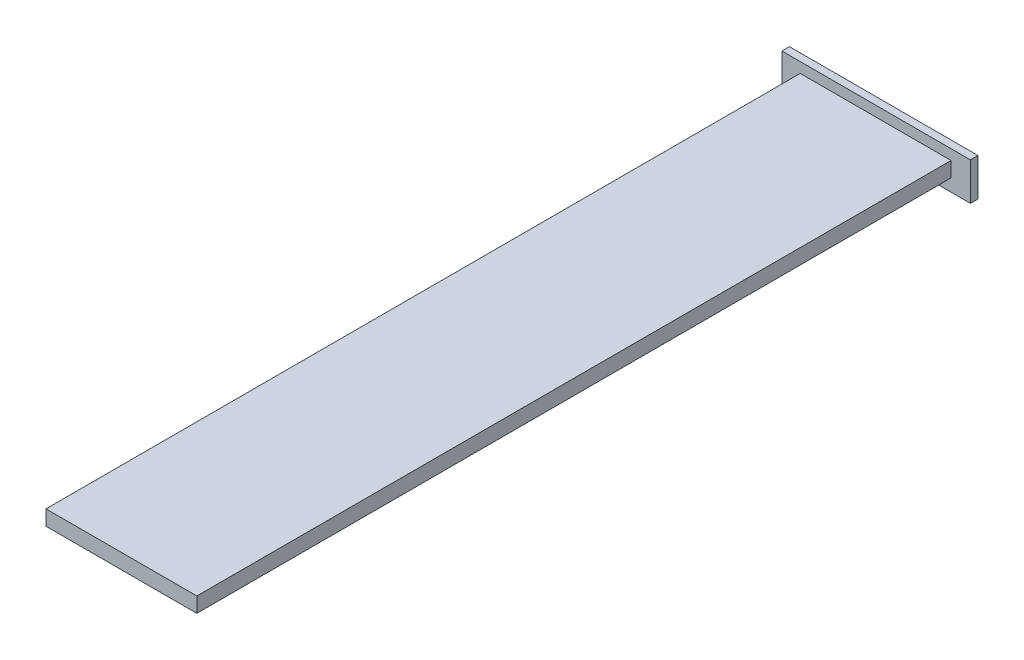
SolidWorks part; units mm, degrees
material "AISI 1010 Aço, barra laminada a quente"
ref_plane "Plano frontal" through (0, 0, 0) normal (0, 0, 1) x (1, 0, 0)
ref_plane "Plano superior" through (0, 0, 0) normal (0, 1, 0) x (1, 0, 0)
ref_plane "Plano direito" through (0, 0, 0) normal (1, 0, 0) x (0, 0, -1)
sketch "Esboço2" plane through (0, 0, 0) normal (0, 0, 1) x (1, 0, 0)
  line L1 (0, 0) -> (250, 0)
  line L2 (0, 0) -> (0, 50)
  line L3 (0, 50) -> (250, 50)
  line L4 (250, 0) -> (250, 50)
  dimension "D1" = 50
  dimension "D2" = 250
extrude "Ressalto-extrusão1" add sketch "Esboço2" along normal blind 10
sketch "Esboço4" plane through (0, 0, 10) normal (0, 0, 1) x (1, 0, 0)
  line L1 (24.2879, 36.4076) -> (224.2879, 36.4076)
  line L2 (24.2879, 36.4076) -> (24.2879, 16.4076)
  line L3 (24.2879, 16.4076) -> (224.2879, 16.4076)
  line L4 (224.2879, 36.4076) -> (224.2879, 16.4076)
  line L5 (24.2879, 36.4076) -> (224.2879, 16.4076) construction
  line L6 (24.2879, 16.4076) -> (224.2879, 36.4076) construction
  point P0 (124.2879, 26.4076)
  dimension "D1" = 200
  dimension "D2" = 20
extrude "Ressalto-extrusão2" add sketch "Esboço4" along normal blind 1000
